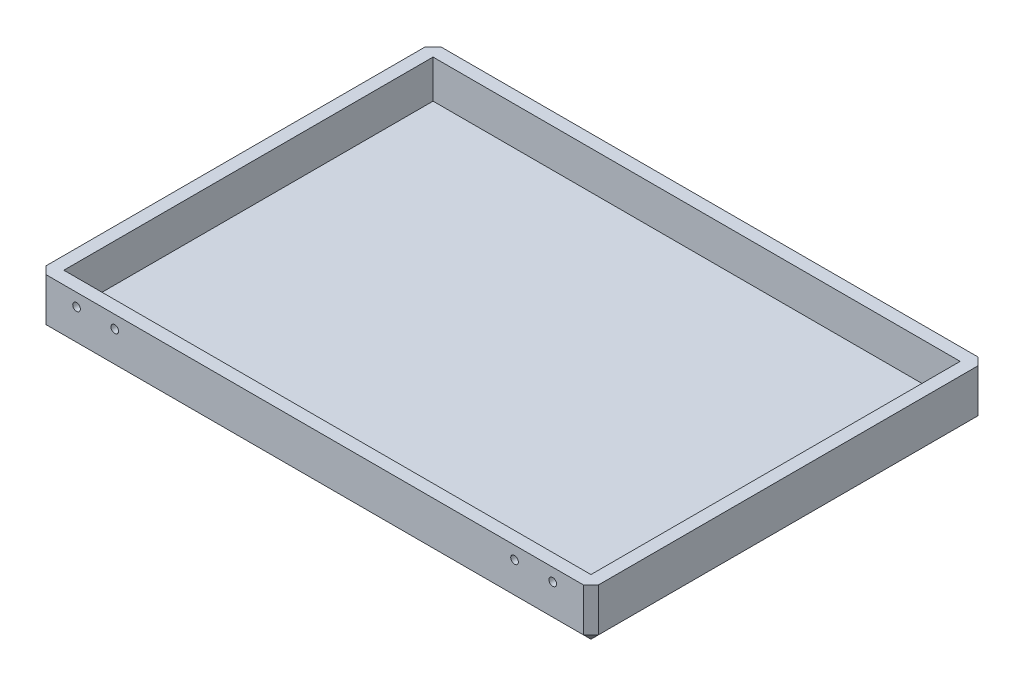
SolidWorks part; units mm, degrees
ref_plane "Vorne" through (0, 0, 0) normal (0, 0, 1) x (1, 0, 0)
ref_plane "Oben" through (0, 0, 0) normal (0, 1, 0) x (1, 0, 0)
ref_plane "Rechts" through (0, 0, 0) normal (1, 0, 0) x (0, 0, -1)
sketch "Skizze2" plane through (0, 0, 0) normal (0, 1, 0) x (1, 0, 0)
  line L1 (-108.5, 77.5) -> (108.5, 77.5)
  line L2 (-108.5, 77.5) -> (-108.5, -77.5)
  line L3 (-108.5, -77.5) -> (108.5, -77.5)
  line L4 (108.5, 77.5) -> (108.5, -77.5)
  line L5 (-108.5, 77.5) -> (108.5, -77.5) construction
  line L6 (-108.5, -77.5) -> (108.5, 77.5) construction
  point P0 (0, 0)
  dimension "D1" = 217
  dimension "D2" = 155
extrude "Aufsatz-Linear austragen1" add sketch "Skizze2" along normal blind 20
shell "Wandung1" thickness 5
sketch "Skizze7" plane through (0, 0, 77.5) normal (0, 0, 1) x (1, 0, 0)
  line L1 (-108.5, 20) -> (-108.5, 0) construction
  line L2 (-108.5, 20) -> (108.5, 20) construction
  line L3 (0, -11) -> (0, 11) construction
  circle A0 centre (-93.5, 15) radius 1.5
  circle A2 centre (-78.5, 15) radius 1.5
  circle A4 centre (78.5, 15) radius 1.5
  circle A5 centre (93.5, 15) radius 1.5
  dimension "D1" = 3
  dimension "D2" = 3
  dimension "D3" = 5
  dimension "D4" = 5
  dimension "D5" = 15
  dimension "D6" = 15
extrude "Schnitt-Linear austragen1" cut sketch "Skizze7" against normal up to next
chamfer "Fase1" distance 3 angle 45 8 edges at (-108.5, 10, -77.5) (-108.5, 10, 77.5) (108.5, 10, -77.5) (108.5, 10, 77.5) (0, 0, 77.5) (108.5, 0, 0) (0, 0, -77.5) (-108.5, 0, 0)
sketch "Skizze8" plane through (0, 0, 0) normal (0, -1, 0) x (1, 0, 0)
  line L0 (-96.8812, -69.2) -> (-96.8812, -62.8)
  line L1 (-97.441, -59.2017) -> (-98.5081, -61.05)
  line L2 (-98.2483, -61.5) -> (-97.1812, -61.5)
  line L3 (-86.5222, -61.95) -> (-90.3214, -68.5304)
  line L4 (-90.8812, -68.3804) -> (-90.8812, -62.8)
  line L5 (-95.8812, -55.6196) -> (-95.8812, -61.2)
  line L7 (-96.441, -55.4696) -> (-100.2402, -62.05)
  line L8 (-99.9804, -62.5) -> (-97.1812, -62.5)
  line L9 (-88.2543, -62.95) -> (-89.3214, -64.7983)
  line L10 (-89.8812, -64.6483) -> (-89.8812, -62.8)
  line L11 (-95.5812, -61.5) -> (-91.1812, -61.5)
  line L12 (-95.5812, -62.5) -> (-91.1812, -62.5)
  line L13 (-96.8812, -61.2) -> (-96.8812, -59.3517)
  line L14 (-95.8812, -62.8) -> (-95.8812, -69.2)
  line L15 (-90.8812, -61.2) -> (-90.8812, -54.8)
  line L16 (-89.8812, -61.2) -> (-89.8812, -54.8)
  line L17 (-89.5812, -61.5) -> (-86.782, -61.5)
  line L18 (-89.5812, -62.5) -> (-88.5141, -62.5)
  line L19 (-96.5812, -69.5) -> (-96.1812, -69.5)
  line L20 (-90.5812, -54.5) -> (-90.1812, -54.5)
  line L21 (-105.5, 74.5) -> (-105.5, -74.5) construction
  line L22 (-105.5, -74.5) -> (105.5, -74.5) construction
  arc A0 (-96.8812, -69.2) -> (-96.5812, -69.5) centre (-96.5812, -69.2) ccw
  arc A1 (-96.1812, -69.5) -> (-95.8812, -69.2) centre (-96.1812, -69.2) ccw
  arc A2 (-95.5812, -62.5) -> (-95.8812, -62.8) centre (-95.5812, -62.8) ccw
  arc A3 (-90.3214, -68.5304) -> (-90.8812, -68.3804) centre (-90.5812, -68.3804) cw
  arc A4 (-90.8812, -62.8) -> (-91.1812, -62.5) centre (-91.1812, -62.8) ccw
  arc A5 (-89.8812, -62.8) -> (-89.5812, -62.5) centre (-89.5812, -62.8) cw
  arc A6 (-89.3214, -64.7983) -> (-89.8812, -64.6483) centre (-89.5812, -64.6483) cw
  arc A7 (-88.5141, -62.5) -> (-88.2543, -62.95) centre (-88.5141, -62.8) cw
  arc A8 (-86.782, -61.5) -> (-86.5222, -61.95) centre (-86.782, -61.8) cw
  arc A9 (-89.8812, -61.2) -> (-89.5812, -61.5) centre (-89.5812, -61.2) ccw
  arc A10 (-90.8812, -61.2) -> (-91.1812, -61.5) centre (-91.1812, -61.2) cw
  arc A11 (-95.5812, -61.5) -> (-95.8812, -61.2) centre (-95.5812, -61.2) cw
  arc A12 (-97.1812, -62.5) -> (-96.8812, -62.8) centre (-97.1812, -62.8) cw
  arc A13 (-100.2402, -62.05) -> (-99.9804, -62.5) centre (-99.9804, -62.2) ccw
  arc A14 (-98.5081, -61.05) -> (-98.2483, -61.5) centre (-98.2483, -61.2) ccw
  arc A15 (-97.1812, -61.5) -> (-96.8812, -61.2) centre (-97.1812, -61.2) ccw
  arc A16 (-96.8812, -59.3517) -> (-97.441, -59.2017) centre (-97.1812, -59.3517) ccw
  arc A17 (-90.1812, -54.5) -> (-89.8812, -54.8) centre (-90.1812, -54.8) cw
  arc A18 (-90.5812, -54.5) -> (-90.8812, -54.8) centre (-90.5812, -54.8) ccw
  arc A19 (-95.8812, -55.6196) -> (-96.441, -55.4696) centre (-96.1812, -55.6196) ccw
  point P7 (-96.4545, -56.5691)
  point P21 (-96.256, -57.3639)
  point P22 (0, 0)
  point P23 (0, 0)
  point P24 (0, 0)
  point P25 (0, 0)
  point P26 (0, 0)
  point P27 (0, 0)
  point P34 (-96.8812, -69.5)
  point P37 (-95.8812, -69.5)
  point P40 (-95.8812, -62.5)
  point P43 (-90.8812, -69.5)
  point P48 (-89.8812, -62.5)
  point P57 (-89.8812, -61.5)
  point P60 (-90.8812, -61.5)
  point P63 (-95.8812, -61.5)
  point P66 (-96.8812, -62.5)
  point P69 (-100.5, -62.5)
  point P74 (-96.8812, -61.5)
  point P79 (-89.8812, -54.5)
  point P82 (-90.8812, -54.5)
  point P85 (-95.8812, -54.5)
  point P86 (0, 0)
  point P87 (0, 0)
  dimension "D13" = 0.3
  dimension "D1" = 60
  dimension "D2" = 60
  dimension "D3" = 1
  dimension "D4" = 1
  dimension "D5" = 1
  dimension "D6" = 1
  dimension "D7" = 1
  dimension "D8" = 7
  dimension "D9" = 7
  dimension "D10" = 5
  dimension "D11" = 5
  dimension "D12" = 5
extrude "Schnitt-Linear austragen2" cut sketch "Skizze8" against normal blind 1
